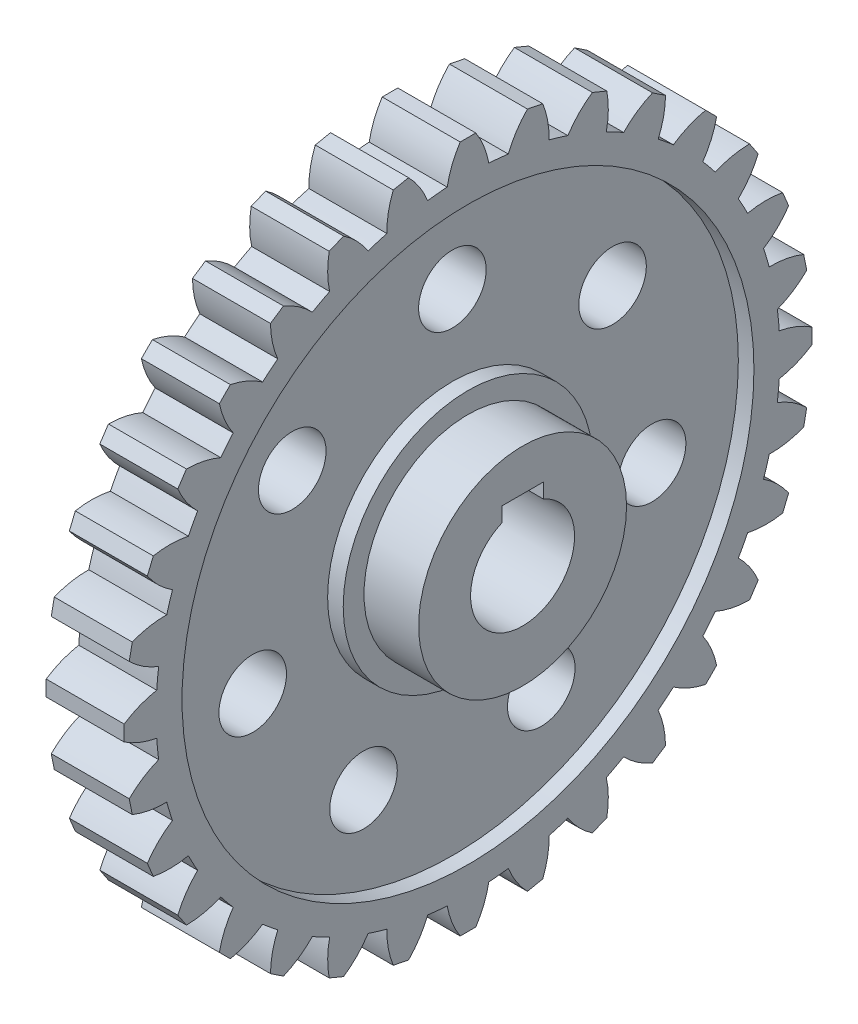
SolidWorks part; units mm, degrees
ref_plane "Front Plane" through (0, 0, 0) normal (0, 0, 1) x (1, 0, 0)
ref_plane "Top Plane" through (0, 0, 0) normal (0, 1, 0) x (1, 0, 0)
ref_plane "Right Plane" through (0, 0, 0) normal (1, 0, 0) x (0, 0, -1)
sketch "Sketch1" plane through (0, 0, 0) normal (1, 0, 0) x (0, 0, -1)
  circle A0 centre (0, 0) radius 60
  dimension "D1" = 120
extrude "Boss-Extrude1" add sketch "Sketch1" along normal mid plane 15
sketch "Sketch2" plane through (7.5, 0, 0) normal (1, 0, 0) x (0, 0, -1)
  line L0 (0, 0) -> (0, 74.7802) construction
  line L1 (-1.5, 66.1335) -> (1.5, 66.1335)
  arc A0 (4, 59.8665) -> (-4, 59.8665) centre (0, 0) ccw
  circle A1 centre (0, 0) radius 60 construction
  arc A2 (-4, 59.8665) -> (-1.5, 66.1335) centre (12.726, 56.8264) cw
  arc A3 (4, 59.8665) -> (1.5, 66.1335) centre (-12.726, 56.8264) ccw
  dimension "D4" = 17
  dimension "D1" = 1.5
  dimension "D2" = 4
  dimension "D3" = 6.267
extrude "Boss-Extrude2" add sketch "Sketch2" against normal up to surface (15 mm away) up to face at (-7.5, 0, -60)
pattern_circular "CirPattern1" count 32 over 360 about axis through (0, 0, 0) along (1, 0, 0) of "Boss-Extrude2"
sketch "Sketch4" plane through (0, 0, 0) normal (1, 0, 0) x (0, 0, -1)
  circle A0 centre (0, 0) radius 20
  dimension "D1" = 40
extrude "Boss-Extrude3" add sketch "Sketch4" along normal mid plane 36
sketch "Sketch5" plane through (18, 0, 0) normal (1, 0, 0) x (0, 0, -1)
  line L0 (0, 0) -> (0, 16.5091) construction
  line L1 (-4, 12) -> (4, 12)
  line L2 (-4, 12) -> (-4, 9.1652)
  line L3 (4, 12) -> (4, 9.1652)
  arc A0 (-4, 9.1652) -> (4, 9.1652) centre (0, 0) ccw
  dimension "D1" = 20
  dimension "D2" = 8
  dimension "D3" = 12
extrude "Cut-Extrude1" cut sketch "Sketch5" against normal through all and the other way through all
sketch "Sketch6" plane through (7.5, 0, 0) normal (1, 0, 0) x (0, 0, -1)
  circle A0 centre (0, 0) radius 55
  circle A1 centre (0, 0) radius 24
  dimension "D1" = 110
  dimension "D2" = 48
extrude "Cut-Extrude2" cut sketch "Sketch6" against normal blind 3
sketch "Sketch7" plane through (4.5, 0, 0) normal (1, 0, 0) x (0, 0, -1)
  circle A0 centre (0, 0) radius 39.4 construction
  circle A1 centre (0, 39.4) radius 6.5
  circle A2 centre (30.8042, 24.5655) radius 6.5
  circle A3 centre (38.4122, -8.7673) radius 6.5
  circle A4 centre (17.095, -35.4982) radius 6.5
  circle A5 centre (-17.095, -35.4982) radius 6.5
  circle A6 centre (-38.4122, -8.7673) radius 6.5
  circle A7 centre (-30.8042, 24.5655) radius 6.5
  point P19 (0, 0)
  dimension "D1" = 78.8
  dimension "D2" = 13
  dimension "D3" = 7
extrude "Cut-Extrude3" cut sketch "Sketch7" against normal through all
